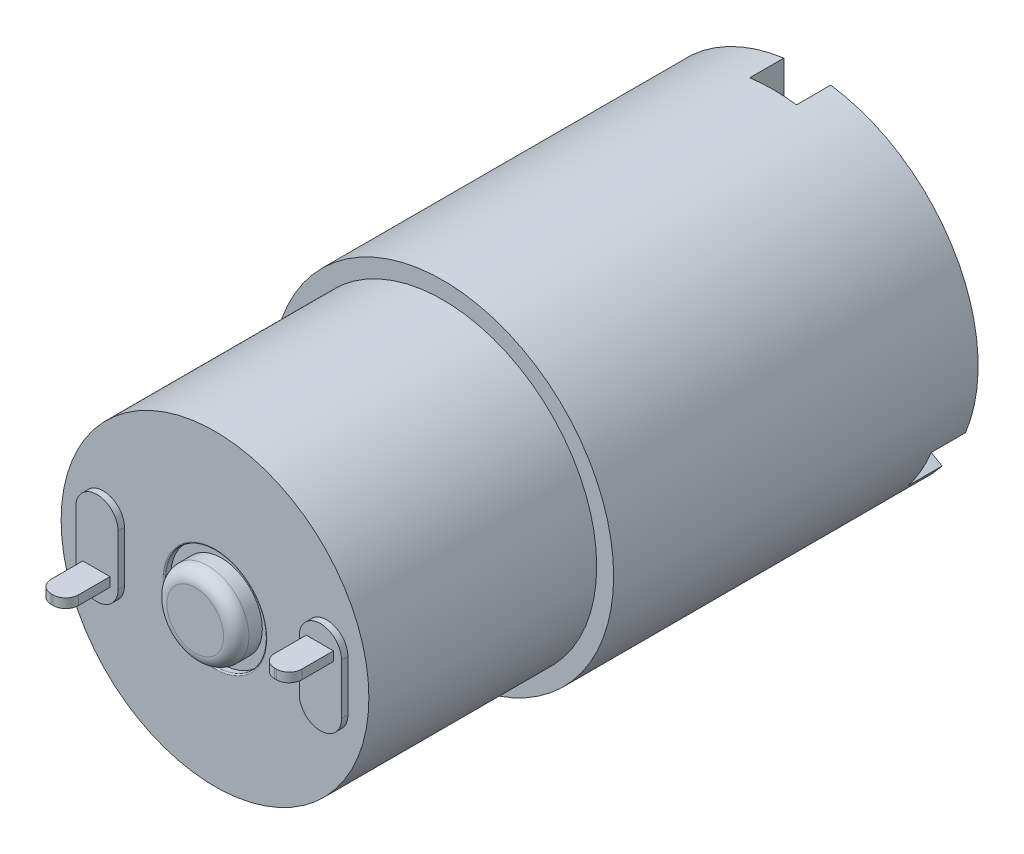
SolidWorks part; units mm, degrees
ref_plane "前视基准面" through (0, 0, 0) normal (0, 0, 1) x (1, 0, 0)
ref_plane "上视基准面" through (0, 0, 0) normal (0, 1, 0) x (1, 0, 0)
ref_plane "右视基准面" through (0, 0, 0) normal (1, 0, 0) x (0, 0, -1)
sketch "草图1" plane through (0, 0, 0) normal (0, 0, 1) x (1, 0, 0)
  circle A0 centre (0, 0) radius 13.5
  dimension "D1" = 27
extrude "凸台-拉伸1" add sketch "草图1" along normal blind 28.8
sketch "草图2" plane through (0, 0, 28.8) normal (0, 0, 1) x (1, 0, 0)
  circle A0 centre (0, 0) radius 12.16
  dimension "D1" = 24.32
extrude "凸台-拉伸2" add sketch "草图2" along normal blind 18
sketch "草图3" plane through (0, 0, 46.8) normal (0, 0, 1) x (1, 0, 0)
  circle A0 centre (0, 0) radius 4
extrude "切除-拉伸1" cut sketch "草图3" against normal blind 0.5
sketch "草图4" plane through (0, 0, 46.3) normal (0, 0, 1) x (1, 0, 0)
  circle A0 centre (0, 0) radius 3.24
  dimension "D1" = 6.48
extrude "凸台-拉伸3" add sketch "草图4" along normal blind 2.06
fillet "圆角1" radius 0.1 1 edges at (4, 0, 46.8)
fillet "圆角2" radius 1 1 edges at (3.24, 0, 48.36)
sketch "草图5" plane through (0, 0, 46.8) normal (0, 0, 1) x (1, 0, 0)
  line L0 (-8.83, 2) -> (-8.83, -2) construction
  line L1 (-7.16, 2) -> (-7.16, -2)
  line L2 (-10.5, 2) -> (-10.5, -2)
  line L3 (0, 9.4702) -> (0, -9.983) construction
  line L4 (-16.2843, 0) -> (20.4973, 0) construction
  line L5 (8.83, 2) -> (8.83, -2) construction
  line L6 (7.16, 2) -> (7.16, -2)
  line L7 (10.5, 2) -> (10.5, -2)
  arc A0 (-7.16, 2) -> (-10.5, 2) centre (-8.83, 2) ccw
  arc A1 (-10.5, -2) -> (-7.16, -2) centre (-8.83, -2) ccw
  arc A2 (7.16, 2) -> (10.5, 2) centre (8.83, 2) cw
  arc A3 (10.5, -2) -> (7.16, -2) centre (8.83, -2) cw
  point P2 (-8.83, 0)
  point P12 (0, 0)
  point P15 (8.83, 0)
  dimension "D1" = 3.34
  dimension "D2" = 4
  dimension "D3" = 21
extrude "凸台-拉伸4" add sketch "草图5" along normal blind 0.5
sketch "草图6" plane through (0, 0, 47.3) normal (0, 0, 1) x (1, 0, 0)
  line L0 (-9.9422, -1.4355) -> (-7.797, -1.4355)
  line L1 (7.7117, 2.3123) -> (9.8569, 2.3123)
  line L2 (7.7117, 2.3123) -> (7.7117, 1.5805)
  line L3 (7.7117, 1.5805) -> (9.8569, 1.5805)
  line L4 (9.8569, 2.3123) -> (9.8569, 1.5805)
  line L5 (-9.9422, -1.4355) -> (-9.9422, -2.1674)
  line L6 (-9.9422, -2.1674) -> (-7.797, -2.1674)
  line L7 (-7.797, -1.4355) -> (-7.797, -2.1674)
  point P4 (-7.532, -2.4071)
extrude "凸台-拉伸5" add sketch "草图6" along normal blind 3.5
fillet "圆角3" radius 1 4 edges at (9.8569, 1.9464, 50.8) (7.7117, 1.9464, 50.8) (-7.797, -1.8014, 50.8) (-9.9422, -1.8014, 50.8)
sketch "草图7" plane through (0, 0, 0) normal (0, 0, -1) x (-1, 0, 0)
  line L0 (0, 16) -> (0, 11) construction
  line L1 (1.85, 16) -> (1.85, 11)
  line L2 (-1.85, 16) -> (-1.85, 11)
  line L3 (13.8564, -8) -> (9.5263, -5.5) construction
  line L4 (12.9314, -9.6021) -> (8.6013, -7.1021)
  line L5 (14.7814, -6.3979) -> (10.4513, -3.8979)
  line L6 (-13.8564, -8) -> (-9.5263, -5.5) construction
  line L7 (-14.7814, -6.3979) -> (-10.4513, -3.8979)
  line L8 (-12.9314, -9.6021) -> (-8.6013, -7.1021)
  arc A0 (1.85, 16) -> (-1.85, 16) centre (0, 16) ccw
  arc A1 (-1.85, 11) -> (1.85, 11) centre (0, 11) ccw
  circle A2 centre (0, 0) radius 13.5 construction
  arc A3 (12.9314, -9.6021) -> (14.7814, -6.3979) centre (13.8564, -8) ccw
  arc A4 (10.4513, -3.8979) -> (8.6013, -7.1021) centre (9.5263, -5.5) ccw
  arc A5 (-14.7814, -6.3979) -> (-12.9314, -9.6021) centre (-13.8564, -8) ccw
  arc A6 (-8.6013, -7.1021) -> (-10.4513, -3.8979) centre (-9.5263, -5.5) ccw
  point P3 (0, 13.5)
  point P14 (11.6913, -6.75)
  point P21 (-11.6913, -6.75)
  dimension "D1" = 3.7
  dimension "D2" = 2.5
  dimension "D3" = 3
extrude "切除-拉伸2" cut sketch "草图7" against normal blind 2.7
sketch "草图9" plane through (0, 0, 0) normal (0, 1, 0) x (1, 0, 0)
  line L0 (0, 7) -> (0, 0)
  line L1 (0, 0) -> (-2.9057, 0)
  line L2 (-1.85, 0) -> (-13.5, 0) construction
  line L3 (-2.9057, 0) -> (-2, 0.9057)
  line L4 (-2, 0.9057) -> (-2, 3.9496)
  line L5 (-2, 3.9496) -> (-0.8907, 5.059)
  line L6 (-0.8907, 5.059) -> (-2, 5.059)
  line L7 (-2, 5.059) -> (-2, 5.6364)
  line L8 (-2, 5.6364) -> (-0.6364, 7)
  line L9 (-0.6364, 7) -> (0, 7)
  line L10 (0, 8.8735) -> (0, -1.2113) construction
  point P7 (-2.9057, 0)
  dimension "D1" = 2
  dimension "D2" = 45
  dimension "D5" = 7
  dimension "D6" = 135
revolve "旋转1" add sketch "草图9" angle 360 about L10
sketch "草图12" plane through (0, 0, 0) normal (0, 0, -1) x (-1, 0, 0)
  line L0 (0, 12.3277) -> (0, -14.5991) construction
pattern_linear "阵列(线性)1" count 2 spacing 9 along (0, -1, 0) of "旋转1"
sketch "草图10" plane through (0, 0, -7) normal (0, 0, -1) x (-1, 0, 0)
  circle A0 centre (0, 0) radius 0.3231
extrude "切除-拉伸3" cut sketch "草图10" against normal blind 2.7
sketch "草图13" plane through (0, 0, -7) normal (0, 0, -1) x (-1, 0, 0)
  circle A0 centre (0, -9) radius 0.2555
extrude "切除-拉伸4" cut sketch "草图13" against normal blind 2.7
sketch "草图14" plane through (0, 0, 0) normal (0, 0, -1) x (-1, 0, 0)
  line L0 (0, 15.3926) -> (0, -17.5926) construction
  line L1 (-0.5261, 4.9722) -> (-0.5261, 3.4317)
  line L2 (0.5261, 3.4317) -> (0.5261, 4.9722)
  line L3 (2.7089, -2.1715) -> (4.043, -2.9417)
  line L4 (4.5691, -2.0305) -> (3.235, -1.2603)
  line L5 (-3.235, -1.2603) -> (-4.5691, -2.0305)
  line L6 (-4.043, -2.9417) -> (-2.7089, -2.1715)
  arc A0 (4.3636, 4.1181) -> (-4.3636, 4.1181) centre (0, 0) ccw
  arc A1 (3.6364, 3.4317) -> (0.5261, 4.9722) centre (0, 0) ccw
  arc A2 (-4.3636, 4.1181) -> (-3.6364, 3.4317) centre (-4, 3.7749) ccw
  arc A3 (3.6364, 3.4317) -> (4.3636, 4.1181) centre (4, 3.7749) ccw
  arc A4 (-0.5261, 3.4317) -> (0.5261, 3.4317) centre (0, 3.4317) ccw
  circle A5 centre (0, 0) radius 2.9057 construction
  arc A6 (-0.5261, 4.9722) -> (-3.6364, 3.4317) centre (0, 0) ccw
  arc A7 (4.5691, -2.0305) -> (4.7902, 1.4333) centre (0, 0) ccw
  arc A8 (5.7482, 1.72) -> (4.7902, 1.4333) centre (5.2692, 1.5766) ccw
  arc A9 (1.3846, -5.8381) -> (5.7482, 1.72) centre (0, 0) ccw
  arc A10 (1.1538, -4.8651) -> (1.3846, -5.8381) centre (1.2692, -5.3516) ccw
  arc A11 (1.1538, -4.8651) -> (4.043, -2.9417) centre (0, 0) ccw
  arc A12 (3.235, -1.2603) -> (2.7089, -2.1715) centre (2.972, -1.7159) ccw
  arc A13 (-4.043, -2.9417) -> (-1.1538, -4.8651) centre (0, 0) ccw
  arc A14 (-1.3846, -5.8381) -> (-1.1538, -4.8651) centre (-1.2692, -5.3516) ccw
  arc A15 (-5.7482, 1.72) -> (-1.3846, -5.8381) centre (0, 0) ccw
  arc A16 (-4.7902, 1.4333) -> (-5.7482, 1.72) centre (-5.2692, 1.5766) ccw
  arc A17 (-4.7902, 1.4333) -> (-4.5691, -2.0305) centre (0, 0) ccw
  arc A18 (-2.7089, -2.1715) -> (-3.235, -1.2603) centre (-2.972, -1.7159) ccw
  dimension "D1" = 12
  dimension "D2" = 10
  dimension "D4" = 3
  dimension "D3" = 8
extrude "切除-拉伸5" cut sketch "草图14" against normal blind 2
